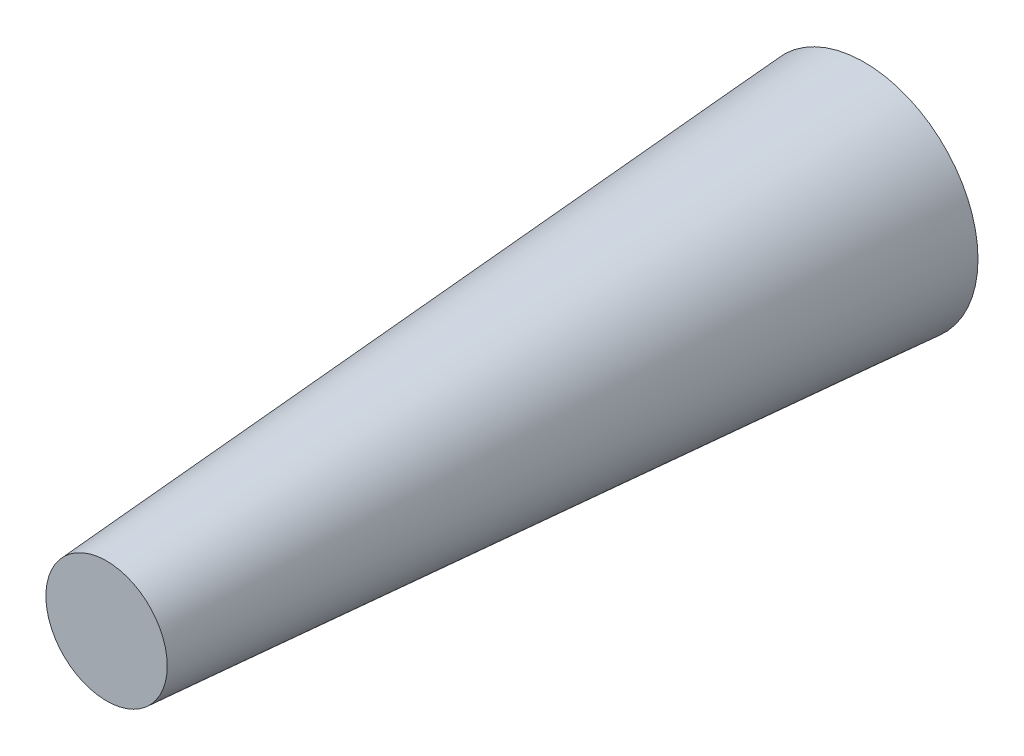
SolidWorks part; units mm, degrees
ref_plane "Front Plane" through (0, 0, 0) normal (0, 0, 1) x (1, 0, 0)
ref_plane "Top Plane" through (0, 0, 0) normal (0, 1, 0) x (1, 0, 0)
ref_plane "Right Plane" through (0, 0, 0) normal (1, 0, 0) x (0, 0, -1)
sketch "Sketch1" plane through (0, 0, 0) normal (0, 0, 1) x (1, 0, 0)
  circle A0 centre (0, 0) radius 1.5
  dimension "D1" = 3
extrude "Boss-Extrude1" add sketch "Sketch1" along normal blind 10 draft 4
